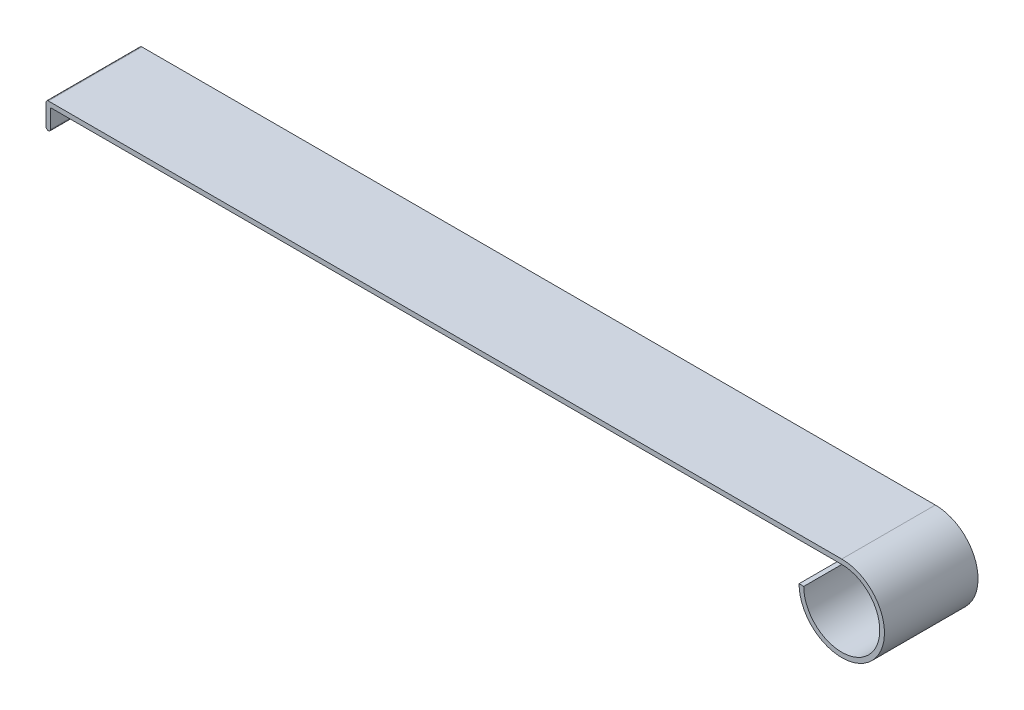
SolidWorks part; units mm, degrees
ref_plane "Plano frontal" through (0, 0, 0) normal (0, 0, 1) x (1, 0, 0)
ref_plane "Plano superior" through (0, 0, 0) normal (0, 1, 0) x (1, 0, 0)
ref_plane "Plano direito" through (0, 0, 0) normal (1, 0, 0) x (0, 0, -1)
sketch "Esboço1" plane through (0, 0, 0) normal (0, 0, 1) x (1, 0, 0)
  line L0 (0.1, 0) -> (0.1, 0.8)
  line L1 (0.1, 0.8) -> (33.0775, 0.8)
  line L2 (-0.1, 0) -> (-0.1, 0.8)
  line L3 (-0.1, 0.8) -> (-0.1, 0.9)
  line L4 (0, 1) -> (33.9081, 1)
  line L5 (33.0775, 0.8) -> (33.9081, 0.8)
  line L6 (32.2834, -0.8247) -> (32.0834, -0.8247)
  arc A0 (-0.1, 0) -> (0.1, 0) centre (0, 0) ccw
  arc A1 (0, 1) -> (-0.1, 0.9) centre (0, 0.9) ccw
  arc A2 (32.0834, -0.8247) -> (33.9081, 1) centre (33.9081, -0.8247) ccw
  arc A3 (32.2834, -0.8247) -> (33.9081, 0.8) centre (33.9081, -0.8247) ccw
  circle A4 centre (33.9081, -0.8247) radius 1.8247 construction
  circle A5 centre (33.9081, -0.8247) radius 1.6247 construction
  dimension "D1" = 0.2
extrude "Ressalto-extrusão1" add sketch "Esboço1" along normal blind 4
